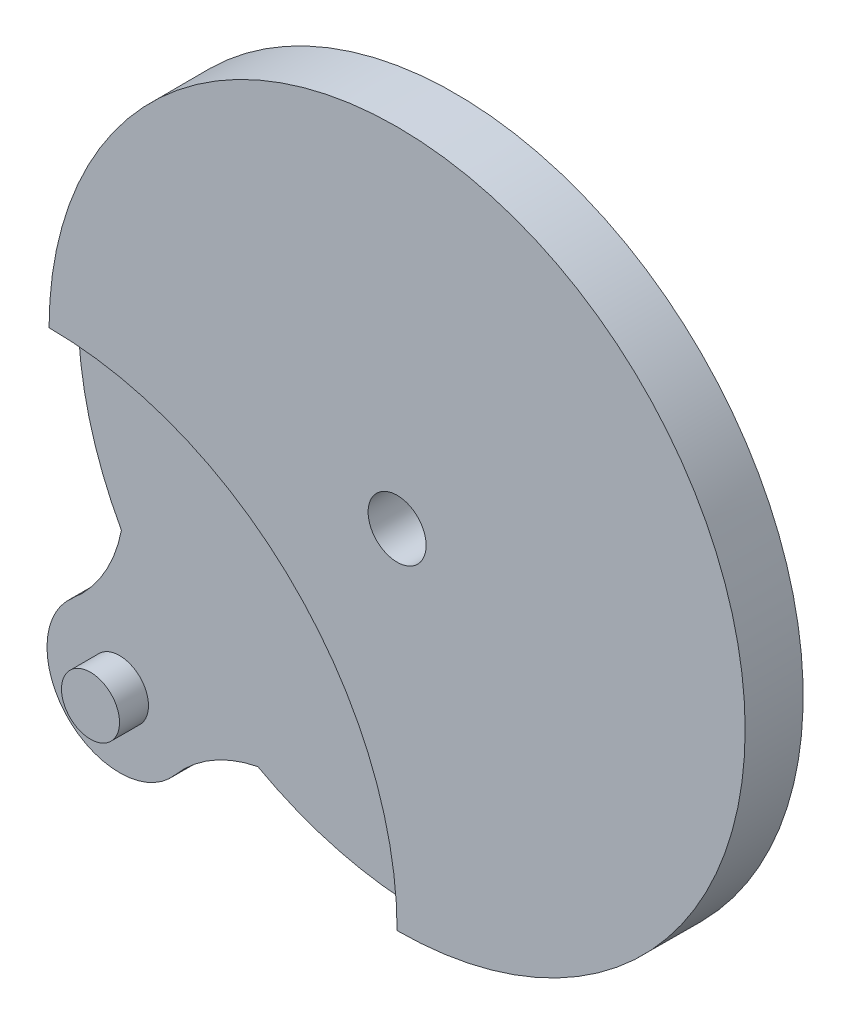
SolidWorks part; units mm, degrees
ref_plane "Přední rovina" through (0, 0, 0) normal (0, 0, 1) x (1, 0, 0)
ref_plane "Horní rovina" through (0, 0, 0) normal (0, 1, 0) x (1, 0, 0)
ref_plane "Pravá rovina" through (0, 0, 0) normal (1, 0, 0) x (0, 0, -1)
sketch "Skica1" plane through (0, 0, 0) normal (0, 0, 1) x (1, 0, 0)
  circle A0 centre (0, 0) radius 60
  circle A1 centre (0, 0) radius 5
  dimension "D1" = 120
  dimension "D2" = 10
extrude "Přidat vysunutím1" add sketch "Skica1" along normal blind 10 contours A0 A1
sketch "Skica2" plane through (0, 0, 10) normal (0, 0, 1) x (1, 0, 0)
  line L2 (-60, 0) -> (-60, -60)
  line L3 (-60, -60) -> (0, -60)
  circle A0 centre (0, 0) radius 60 construction
  arc A1 (-60, 0) -> (0, -60) centre (-60, -60) cw
extrude "Odebrat vysunutím1" cut sketch "Skica2" against normal blind 5
sketch "Skica4" plane through (0, 0, 0) normal (0, 0, -1) x (-1, 0, 0)
  line L0 (66.8921, 0) -> (-59.6923, 0) construction
  line L1 (0, 54.6734) -> (0, -63.7173) construction
  line L2 (-24.5295, 24.5295) -> (78.9724, -78.9724) construction
  circle A0 centre (0, 0) radius 60 construction
  circle A1 centre (0, 0) radius 74.75 construction
  arc A2 (29.0017, -52.5252) -> (52.5252, -29.0017) centre (0, 0) ccw
  arc A3 (43.3093, -60.9251) -> (60.9251, -43.3093) centre (52.8562, -52.8562) ccw
  arc A4 (60.9251, -43.3093) -> (52.5252, -29.0017) centre (77.0628, -24.2155) cw
  arc A5 (43.3093, -60.9251) -> (29.0017, -52.5252) centre (24.2155, -77.0628) ccw
  dimension "D2" = 120
  dimension "D3" = 149.5
  dimension "D4" = 25
  dimension "D5" = 25
  dimension "D6" = 60
  dimension "D1" = 45
extrude "Přidat vysunutím2" add sketch "Skica4" against normal blind 5
sketch "Skica5" plane through (0, 0, 5) normal (0, 0, 1) x (1, 0, 0)
  circle A0 centre (-52.8562, -52.8562) radius 5
  dimension "D1" = 10
extrude "Přidat vysunutím3" add sketch "Skica5" along normal blind 5 contours A0
